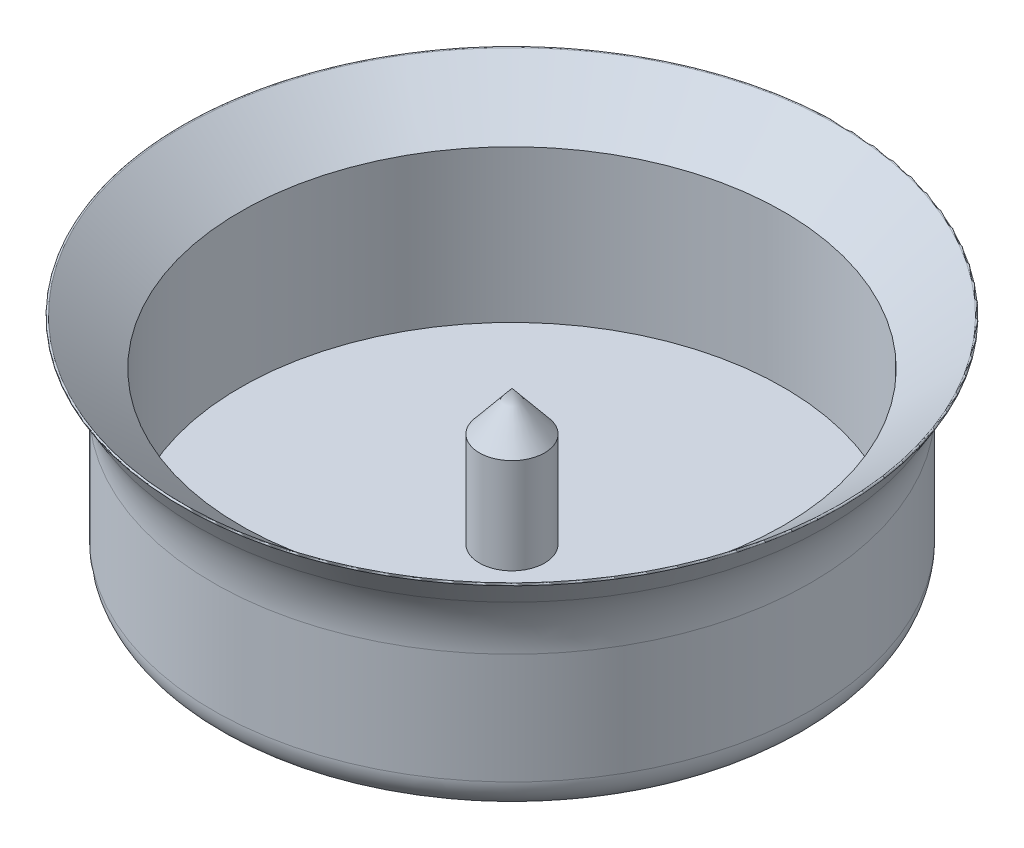
SolidWorks part; units mm, degrees
ref_plane "Front Plane" through (0, 0, 0) normal (0, 0, 1) x (1, 0, 0)
ref_plane "Top Plane" through (0, 0, 0) normal (0, 1, 0) x (1, 0, 0)
ref_plane "Right Plane" through (0, 0, 0) normal (1, 0, 0) x (0, 0, -1)
sketch "Sketch1" plane through (0, 0, 0) normal (0, 0, 1) x (1, 0, 0)
  line L2 (0, 0) -> (0, 14.93)
  line L4 (3, 2.5) -> (3, 11.285)
  line L5 (3, 2.5) -> (25, 2.5)
  line L7 (0, 0) -> (11.9621, 0)
  line L9 (11.9621, 0) -> (27.5, 0)
  line L10 (25, 2.5) -> (25, 16.5)
  line L14 (30.6102, 21.1175) -> (27.5, 15.9579)
  line L15 (30.6102, 21.1175) -> (25, 16.5)
  line L16 (27.5, 15.9579) -> (27.5, 0)
  line L17 (0, 14.93) -> (3, 11.285)
  dimension "D1" = 6
  dimension "D2" = 50
  dimension "D3" = 14
  dimension "D4" = 8.785
  dimension "D5" = 2.5
  dimension "D6" = 2.5
  dimension "D8" = 129.456
  dimension "D9" = 7.266
  dimension "D10" = 6.0245
revolve "Revolve1" add sketch "Sketch1" angle 360 about L2
fillet "Fillet1" radius 10 1 edges at (27.5, 15.9579, 0)
fillet "Fillet2" radius 3 1 edges at (27.5, 0, 0)
fillet "Fillet3" radius 0.1 1 edges at (30.6102, 21.1175, 0)
